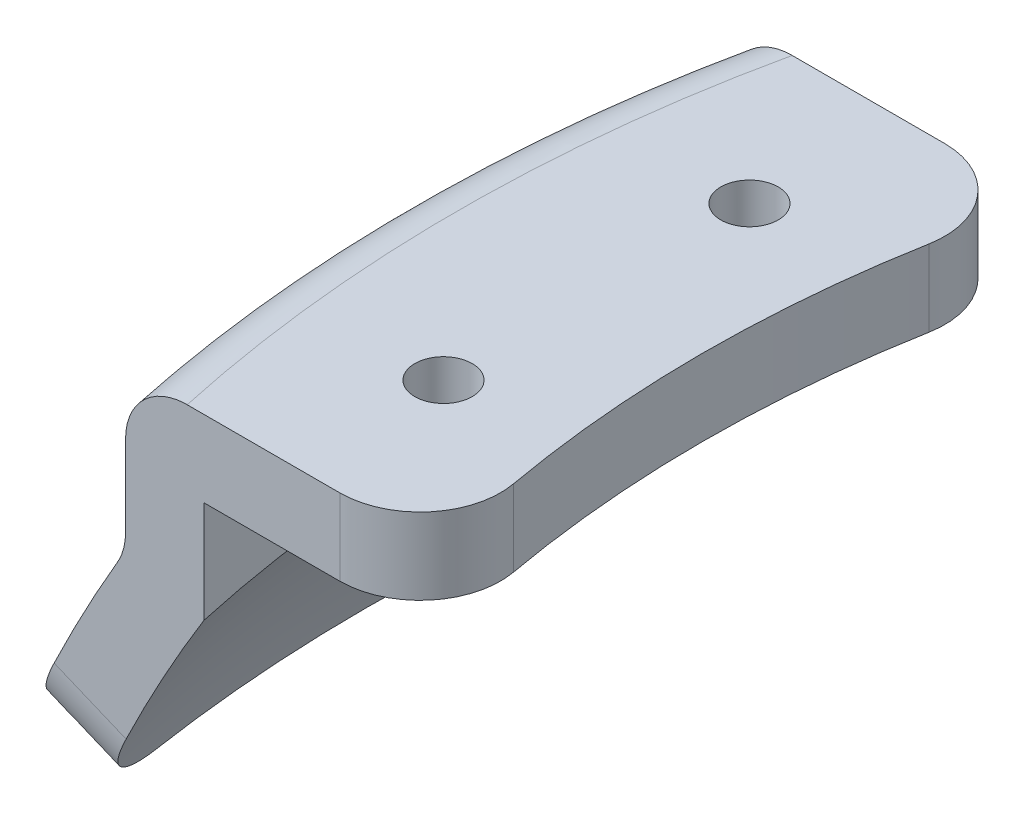
SolidWorks part; units mm, degrees
ref_plane "Front Plane" through (0, 0, 0) normal (0, 0, 1) x (1, 0, 0)
ref_plane "Top Plane" through (0, 0, 0) normal (0, 1, 0) x (1, 0, 0)
ref_plane "Right Plane" through (0, 0, 0) normal (1, 0, 0) x (0, 0, -1)
sketch "Sketch2" plane through (0, 0, 0) normal (0, 0, 1) x (1, 0, 0)
  line L0 (-196.1445, 171.228) -> (-187.3619, 167.5413) construction
  line L1 (-183.6262, 215.8974) -> (-183.6262, 196.285) construction
  line L2 (-174.1012, 206.3724) -> (-174.1012, 193.6724) construction
  line L3 (-145.5262, 206.3724) -> (-174.1012, 206.3724) construction
  line L4 (-145.5262, 206.3724) -> (-145.5262, 215.8974) construction
  line L5 (-145.5262, 215.8974) -> (-183.6262, 215.8974) construction
  line L6 (-196.1445, 171.228) -> (-187.3619, 167.5413)
  line L7 (-183.6262, 215.8974) -> (-183.6262, 196.285)
  line L8 (-174.1012, 206.3724) -> (-174.1012, 193.6724)
  line L9 (-145.5262, 206.3724) -> (-174.1012, 206.3724)
  line L10 (-145.5262, 206.3724) -> (-145.5262, 215.8974)
  line L11 (-145.5262, 215.8974) -> (-183.6262, 215.8974)
  line L12 (0, 0) -> (0, 215.8974) construction
  arc A0 (-183.6262, 196.285) -> (-196.1445, 171.228) centre (0, 88.8917) ccw construction
  arc A1 (-174.1012, 193.6724) -> (-187.3619, 167.5413) centre (0, 88.8917) ccw construction
  arc A2 (-183.6262, 196.285) -> (-196.1445, 171.228) centre (0, 88.8917) ccw
  arc A3 (-174.1012, 193.6724) -> (-187.3619, 167.5413) centre (0, 88.8917) ccw
revolve "Revolve1" add sketch "Sketch2" angle 30 mid plane about L12
fillet "Fillet1" radius 7.5 2 edges at (-183.6262, 196.285, 0) (-183.6262, 215.8974, 0)
sketch "Sketch3" plane through (0, 206.3724, 0) normal (0, -1, 0) x (1, 0, 0)
  circle A0 centre (-158.75, 19.05) radius 3.5719 construction
  circle A1 centre (-158.75, -19.05) radius 3.5719 construction
  circle A2 centre (-158.75, 19.05) radius 3.5719
  circle A3 centre (-158.75, -19.05) radius 3.5719
extrude "Cut-Extrude1" cut sketch "Sketch3" against normal through all both and the other way through all
sketch "Sketch4" plane through (0, 215.8974, 0) normal (0, 1, 0) x (1, 0, 0)
  line L1 (-140.5675, 37.665) -> (-215.4275, 37.665)
  line L2 (-140.5675, 37.665) -> (-140.5675, -37.665)
  line L3 (-140.5675, -37.665) -> (-215.4275, -37.665)
  line L4 (-215.4275, 37.665) -> (-215.4275, -37.665)
  point P5 (-140.5675, -37.665)
extrude "Cut-Extrude2" cut sketch "Sketch4" against normal through all flip side to cut
fillet "Fillet2" radius 10 4 edges at (-140.5675, 211.1349, -37.665) (-140.5675, 211.1349, 37.665)
